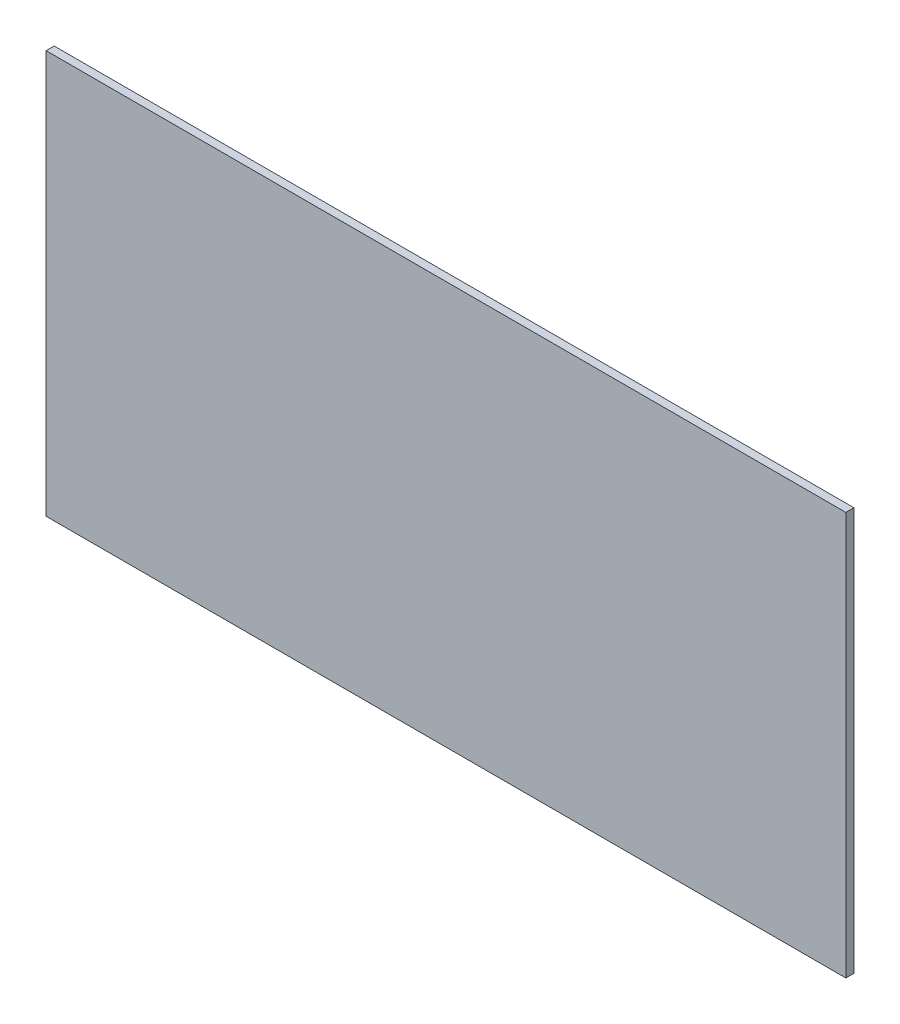
SolidWorks part; units mm, degrees
ref_plane "Спереди" through (0, 0, 0) normal (0, 0, 1) x (1, 0, 0)
ref_plane "Сверху" through (0, 0, 0) normal (0, 1, 0) x (1, 0, 0)
ref_plane "Справа" through (0, 0, 0) normal (1, 0, 0) x (0, 0, -1)
sketch "Эскиз1" plane through (0, 0, 0) normal (0, 0, 1) x (1, 0, 0)
  line L1 (-297.5, 150) -> (297.5, 150)
  line L2 (-297.5, 150) -> (-297.5, -150)
  line L3 (-297.5, -150) -> (297.5, -150)
  line L4 (297.5, 150) -> (297.5, -150)
  line L5 (-297.5, 150) -> (297.5, -150) construction
  line L6 (-297.5, -150) -> (297.5, 150) construction
  point P0 (0, 0)
  dimension "D1" = 595
  dimension "D2" = 300
extrude "Бобышка-Вытянуть1" add sketch "Эскиз1" along normal blind 6
